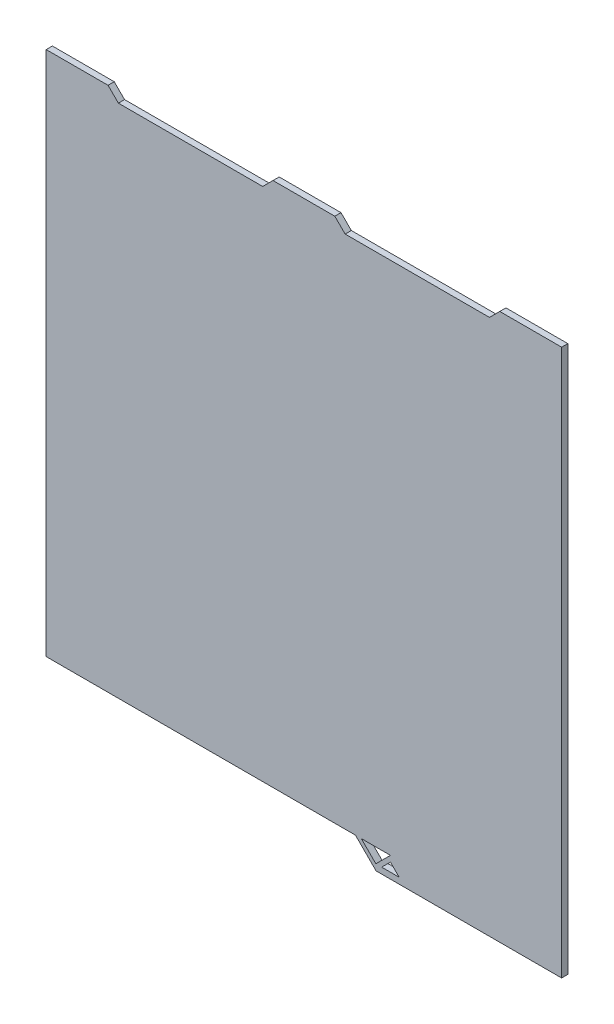
SolidWorks part; units mm, degrees
ref_plane "Front Plane" through (0, 0, 0) normal (0, 0, 1) x (1, 0, 0)
ref_plane "Top Plane" through (0, 0, 0) normal (0, 1, 0) x (1, 0, 0)
ref_plane "Right Plane" through (0, 0, 0) normal (1, 0, 0) x (0, 0, -1)
sketch "Sketch3" plane through (0, 0, 0) normal (0, 0, 1) x (1, 0, 0)
  line L1 (-125, 125) -> (-125, -125)
  line L2 (-125, -125) -> (25, -125)
  line L3 (125, 125) -> (125, -125)
  line L7 (90, 125) -> (20, 125)
  line L8 (35, -135) -> (25, -125)
  line L10 (125, -125) -> (125, -135)
  line L11 (125, -135) -> (35, -135)
  line L14 (-95, 130) -> (-90, 125)
  line L16 (-125, 125) -> (-125, 130)
  line L17 (-125, 130) -> (-95, 130)
  line L20 (125, 125) -> (125, 130)
  line L21 (125, 130) -> (95, 130)
  line L23 (95, 130) -> (90, 125)
  line L24 (-20, 125) -> (-90, 125)
  line L27 (-15, 130) -> (15, 130)
  line L29 (-15, 130) -> (-20, 125)
  line L30 (15, 130) -> (20, 125)
  dimension "D1" = 250
  dimension "D3" = 125
  dimension "D4" = 125
  dimension "D2" = 250
  dimension "D5" = 10
  dimension "D6" = 90
  dimension "D7" = 150
  dimension "D8" = 10
  dimension "D9" = 5
  dimension "D10" = 30
  dimension "D11" = 5
  dimension "D12" = 30
  dimension "D14" = 5
  dimension "D15" = 135
  dimension "D13" = 135
  dimension "D16" = 5
  dimension "D18" = 30
  dimension "D19" = 110
  dimension "D20" = 135
  dimension "D17" = 5
  dimension "D21" = 135
extrude "Boss-Extrude5" add sketch "Sketch3" against normal blind 3
sketch "Sketch4" plane through (0, 0, 0) normal (0, 0, 1) x (1, 0, 0)
  line L0 (34.8995, -132.0711) -> (41.9706, -125)
  line L2 (27.8284, -125) -> (34.8995, -132.0711)
  line L4 (27.8284, -125) -> (41.9706, -125)
  line L5 (25, -125) -> (35, -135) construction
  line L6 (37.7279, -132.0711) -> (46.2132, -132.0711)
  line L8 (37.7279, -132.0711) -> (41.9706, -127.8284)
  line L9 (46.2132, -132.0711) -> (41.9706, -127.8284)
  dimension "D1" = 2
  dimension "D2" = 10
  dimension "D3" = 10
  dimension "D5" = 2
  dimension "D6" = 6
  dimension "D4" = 6
extrude "Cut-Extrude1" cut sketch "Sketch4" against normal blind 9
equation "\"D3@Sketch3\"=\"D2@Sketch3\"/2"
equation "\"D4@Sketch3\"=\"D1@Sketch3\"/2"
equation "\"D6@Sketch4\"=\"D4@Sketch4\""
equation "\"D12@Sketch3\"=\"D10@Sketch3\""
equation "\"D18@Sketch3\"=\"D10@Sketch3\""
equation "\"D19@Sketch3\"=(\"D2@Sketch3\"-\"D18@Sketch3\")/2"
